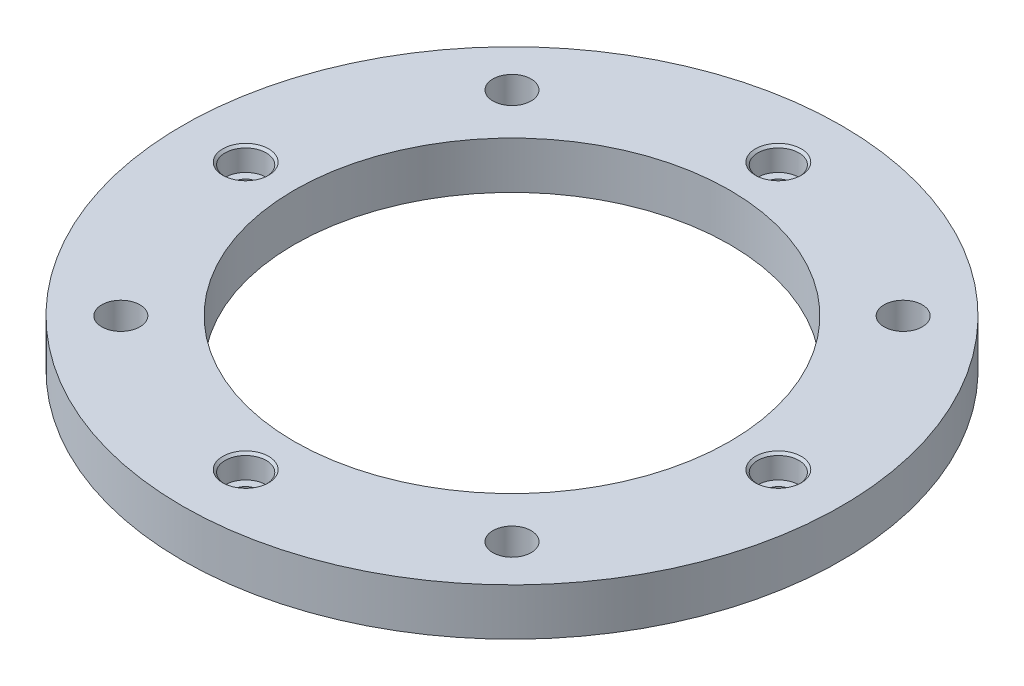
SolidWorks part; units mm, degrees
ref_plane "Front Plane" through (0, 0, 0) normal (0, 0, 1) x (1, 0, 0)
ref_plane "Top Plane" through (0, 0, 0) normal (0, 1, 0) x (1, 0, 0)
ref_plane "Right Plane" through (0, 0, 0) normal (1, 0, 0) x (0, 0, -1)
sketch "Sketch1" plane through (0, 0, 0) normal (0, 1, 0) x (1, 0, 0)
  line L1 (-88.9, -88.9) -> (88.9, -88.9)
  line L2 (-88.9, -88.9) -> (-88.9, 88.9)
  line L3 (-88.9, 88.9) -> (88.9, 88.9)
  line L4 (88.9, -88.9) -> (88.9, 88.9)
  line L5 (-88.9, -88.9) -> (88.9, 88.9) construction
  line L6 (-88.9, 88.9) -> (88.9, -88.9) construction
  point P0 (0, 0)
  dimension "D1" = 177.8
extrude "Boss-Extrude1" add sketch "Sketch1" along normal blind 12.7
sketch "Sketch2" plane through (0, 12.7, 0) normal (0, 1, 0) x (1, 0, 0)
  line L1 (-52.759, -52.759) -> (52.759, -52.759) construction
  line L2 (-52.759, -52.759) -> (-52.759, 52.759) construction
  line L3 (-52.759, 52.759) -> (52.759, 52.759) construction
  line L4 (52.759, -52.759) -> (52.759, 52.759) construction
  line L5 (-52.759, -52.759) -> (52.759, 52.759) construction
  line L6 (-52.759, 52.759) -> (52.759, -52.759) construction
  circle A0 centre (0, 0) radius 74.6125 construction
  point P3 (-52.759, 52.759)
  point P4 (52.759, 52.759)
  point P5 (52.759, -52.759)
  point P6 (-52.759, -52.759)
  dimension "D1" = 149.225
hole_wizard "13/32 (0.40625) Diameter Hole1" positions "3DSketch1" profile "Sketch3" hole size "13/32" standard "ANSI Inch"
sketch3d "3DSketch1"
  point P0 (-52.759, 12.7, -52.759)
  point P3 (52.759, 12.7, -52.759)
  point P6 (52.759, 12.7, 52.759)
  point P9 (-52.759, 12.7, 52.759)
sketch "Sketch3" plane through (-52.759, 12.7, -52.759) normal (1, 0, 0) x (0, 0, 1)
  line L0 (0, 0) -> (0, 28.5001)
  line L1 (0, 28.5001) -> (5.1594, 25.4)
  line L2 (5.1594, 25.4) -> (5.1594, 0)
  line L5 (5.1594, 0) -> (0, 0)
  line L10 (0, 28.5001) -> (-5.1594, 25.4) construction
  line L11 (0, -6.35) -> (0, 107.95) construction
  dimension "Hole Dia." = 10.3187
  dimension "Hole Depth" = 25.4
  dimension "Drill Angle" = 118
sketch "Sketch4" plane through (0, 12.7, 0) normal (0, 1, 0) x (1, 0, 0)
  circle A0 centre (0, 0) radius 58.7375
  dimension "D1" = 117.475
extrude "Cut-Extrude1" cut sketch "Sketch4" against normal through all
sketch "Sketch5" plane through (0, 12.7, 0) normal (0, 1, 0) x (1, 0, 0)
  line L0 (88.9, 88.9) -> (-88.9, 88.9) construction
  circle A0 centre (0, 0) radius 88.9
extrude "Cut-Extrude2" cut sketch "Sketch5" against normal blind 12.7 flip side to cut
sketch "Sketch6" plane through (0, 12.7, 0) normal (0, 1, 0) x (1, 0, 0)
  line L0 (-71.842, 0) -> (0, 0) construction
  line L1 (0, 0) -> (71.842, 0) construction
  line L2 (71.842, 0) -> (0, 71.842) construction
  line L3 (0, 71.842) -> (0, 0) construction
  line L4 (0, 0) -> (0, -71.842) construction
  point P0 (0, 71.842)
  point P1 (71.842, 0)
  point P4 (-71.842, 0)
  point P5 (0, -71.842)
  dimension "D2" = 101.6
hole_wizard "CBORE for 1/4 Socket Head Cap Screw1" positions "3DSketch2" profile "Sketch9" counterbore size "1/4" standard "ANSI Inch" end condition through all
sketch3d "3DSketch2"
  point P0 (0, 12.7, -71.842)
  point P3 (71.842, 12.7, 0)
  point P6 (-71.842, 12.7, 0)
  point P9 (0, 12.7, 71.842)
sketch "Sketch9" plane through (0, 12.7, -71.842) normal (1, 0, 0) x (0, 0, 1)
  line L0 (0, 0) -> (0, 12.7)
  line L1 (0, 12.7) -> (3.3782, 12.7)
  line L3 (3.3782, 12.7) -> (3.3782, 6.35)
  line L4 (5.5562, 6.35) -> (3.3782, 6.35)
  line L5 (5.5562, 6.35) -> (5.5562, 0.635)
  line L6 (5.5562, 0.635) -> (6.1913, 0)
  line L7 (6.1913, 0) -> (0, 0)
  line L8 (-5.5562, 0.635) -> (-6.1913, 0) construction
  line L11 (0, -6.35) -> (0, 107.95) construction
  dimension "Thru Hole Dia." = 6.7564
  dimension "Thru Hole Depth" = 12.7
  dimension "C'Bore Dia." = 11.1125
  dimension "C'Bore Depth" = 6.35
  dimension "Near C'Sink Dia." = 12.3825
  dimension "Near C'Sink Angle" = 90
